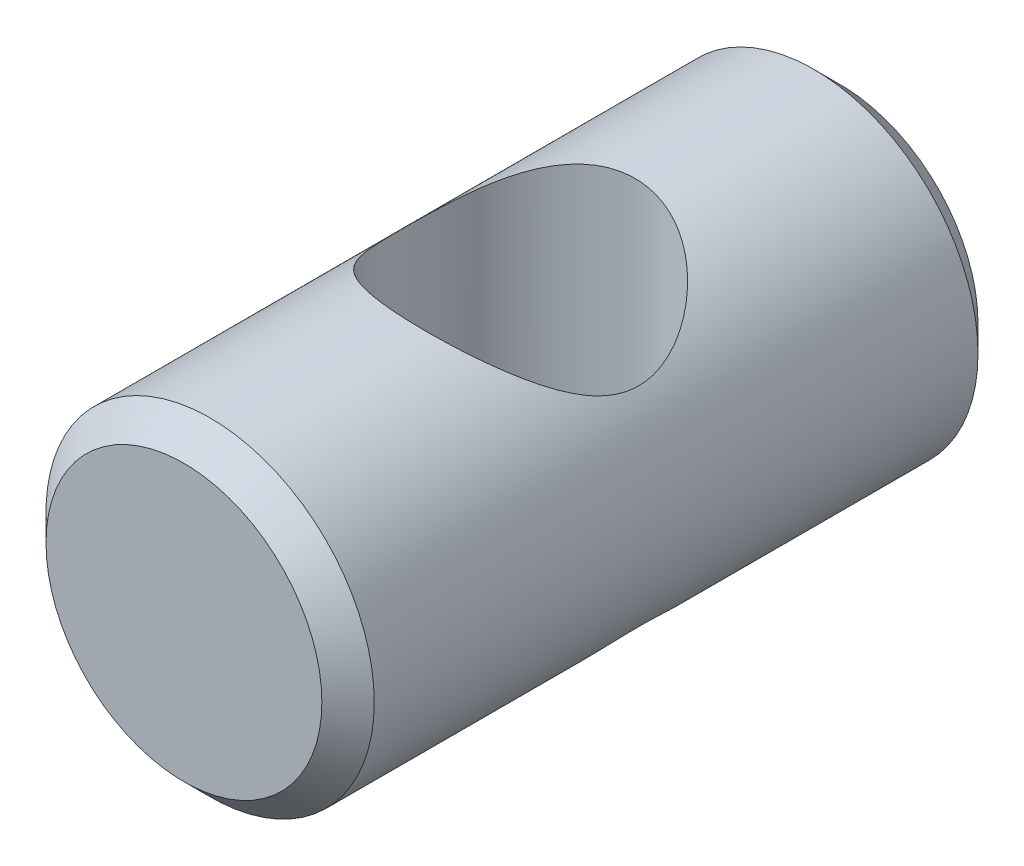
SolidWorks part; units mm, degrees
ref_plane "Front Plane" through (0, 0, 0) normal (0, 0, 1) x (1, 0, 0)
ref_plane "Top Plane" through (0, 0, 0) normal (0, 1, 0) x (1, 0, 0)
ref_plane "Right Plane" through (0, 0, 0) normal (1, 0, 0) x (0, 0, -1)
sketch "Sketch1" plane through (0, 0, 0) normal (0, 0, 1) x (1, 0, 0)
  circle A0 centre (0, 0) radius 4.765
  dimension "D1" = 9.53
extrude "Boss-Extrude1" add sketch "Sketch1" along normal mid plane 19.05
sketch "Sketch2" plane through (0, 0, 0) normal (0, 1, 0) x (1, 0, 0)
  circle A0 centre (0.25, 0) radius 3.43
  dimension "D2" = 6.86
  dimension "D1" = 0.25
extrude "Cut-Extrude1" cut sketch "Sketch2" against normal through all both and the other way through all
chamfer "Chamfer1" distance 0.76 angle 45 2 edges at (4.765, 0, -9.525) (4.765, 0, 9.525)
